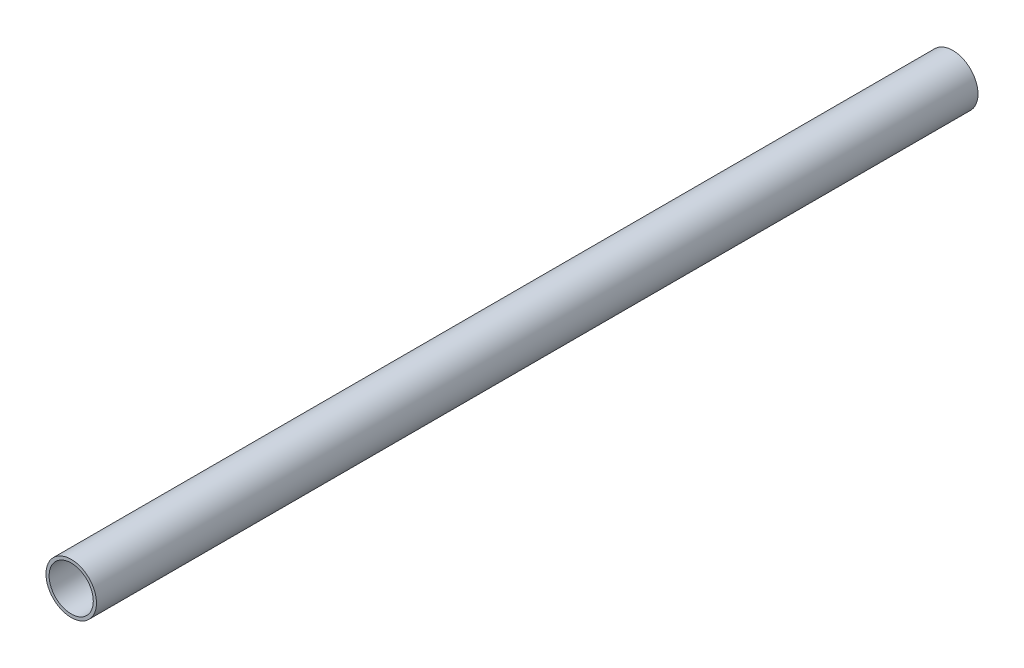
SolidWorks part; units mm, degrees
ref_plane "Front Plane" through (0, 0, 0) normal (0, 0, 1) x (1, 0, 0)
ref_plane "Top Plane" through (0, 0, 0) normal (0, 1, 0) x (1, 0, 0)
ref_plane "Right Plane" through (0, 0, 0) normal (1, 0, 0) x (0, 0, -1)
sketch "Sketch1" plane through (0, 0, 0) normal (0, 0, 1) x (1, 0, 0)
  circle A0 centre (0, 0) radius 7
  circle A1 centre (0, 0) radius 8
  dimension "D2" = 16
  dimension "D1" = 1
extrude "Boss-Extrude1" add sketch "Sketch1" along normal mid plane 279.4
